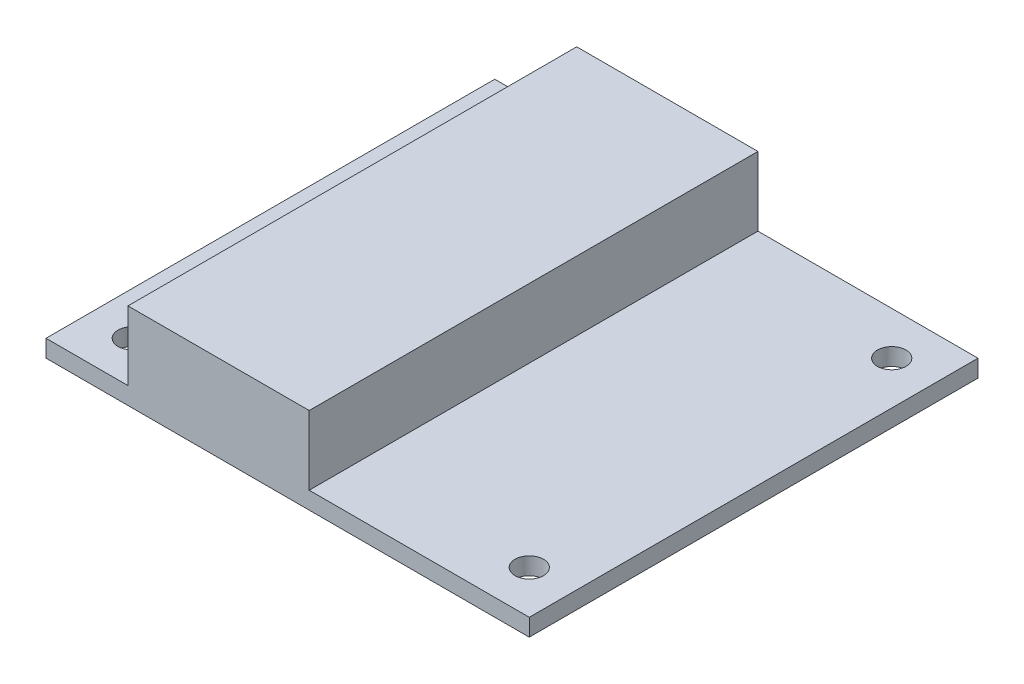
SolidWorks part; units mm, degrees
ref_plane "Front Plane" through (0, 0, 0) normal (0, 0, 1) x (1, 0, 0)
ref_plane "Top Plane" through (0, 0, 0) normal (0, 1, 0) x (1, 0, 0)
ref_plane "Right Plane" through (0, 0, 0) normal (1, 0, 0) x (0, 0, -1)
sketch "Sketch2" plane through (0, 0, 0) normal (0, 1, 0) x (1, 0, 0)
  line L1 (0, 0) -> (56, 0)
  line L2 (0, 0) -> (0, 52)
  line L3 (0, 52) -> (56, 52)
  line L4 (56, 0) -> (56, 52)
  dimension "D1" = 56
  dimension "D2" = 52
extrude "Boss-Extrude1" add sketch "Sketch2" along normal blind 2
sketch "Sketch3" plane through (0, 2, 0) normal (0, 1, 0) x (1, 0, 0)
  line L0 (0, 52) -> (0, 0) construction
  line L1 (56, 52) -> (0, 52) construction
  line L2 (56, 0) -> (56, 52) construction
  line L3 (0, 0) -> (56, 0) construction
  circle A0 centre (5, 47) radius 1.65
  circle A1 centre (51, 47) radius 1.65
  circle A2 centre (5, 5) radius 1.65
  circle A3 centre (51, 5) radius 1.65
  dimension "D3" = 3.3
  dimension "D5" = 3.3
  dimension "D7" = 3.3
  dimension "D8" = 3.3
  dimension "D1" = 5
  dimension "D2" = 5
  dimension "D4" = 5
  dimension "D6" = 5
extrude "Cut-Extrude1" cut sketch "Sketch3" against normal through all
sketch "Sketch4" plane through (0, 2, 0) normal (0, 1, 0) x (1, 0, 0)
  line L0 (56, 52) -> (0, 52) construction
  line L1 (9.5, 52) -> (30.5, 52)
  line L2 (9.5, 52) -> (9.5, 0)
  line L3 (9.5, 0) -> (30.5, 0)
  line L4 (30.5, 52) -> (30.5, 0)
  line L5 (0, 0) -> (56, 0) construction
  line L6 (0, 52) -> (0, 0) construction
  dimension "D1" = 21
  dimension "D2" = 9.5
extrude "Boss-Extrude2" add sketch "Sketch4" along normal blind 8
